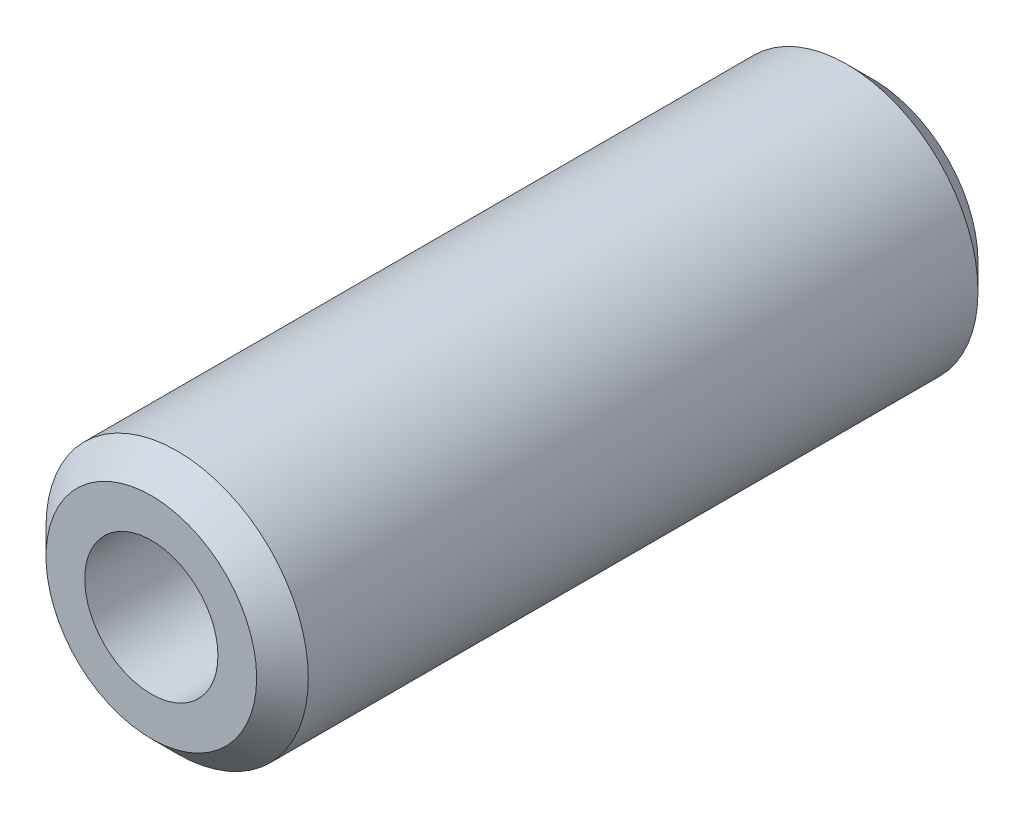
SolidWorks part; units mm, degrees
ref_plane "Front Plane" through (0, 0, 0) normal (0, 0, 1) x (1, 0, 0)
ref_plane "Top Plane" through (0, 0, 0) normal (0, 1, 0) x (1, 0, 0)
ref_plane "Right Plane" through (0, 0, 0) normal (1, 0, 0) x (0, 0, -1)
sketch "Sketch1" plane through (0, 0, 0) normal (0, 0, 1) x (1, 0, 0)
  circle A0 centre (0, 0) radius 6.45
  circle A1 centre (0, 0) radius 12.7
  dimension "D1" = 25.4
  dimension "D2" = 12.9
extrude "Boss-Extrude1" add sketch "Sketch1" along normal mid plane 69.85
chamfer "Chamfer1" distance 2.5 2 edges at (12.7, 0, -34.925) (12.7, 0, 34.925)
